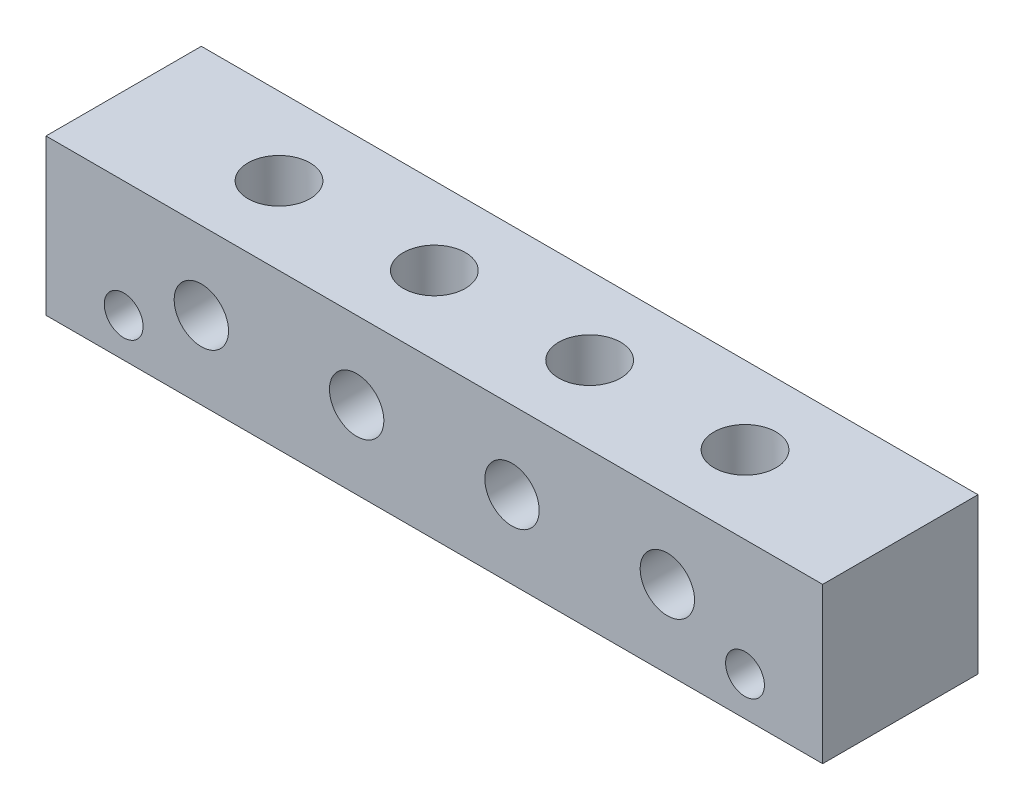
SolidWorks part; units mm, degrees
ref_plane "Plan de face" through (0, 0, 0) normal (0, 0, 1) x (1, 0, 0)
ref_plane "Plan de dessus" through (0, 0, 0) normal (0, 1, 0) x (1, 0, 0)
ref_plane "Plan de droite" through (0, 0, 0) normal (1, 0, 0) x (0, 0, -1)
sketch "Esquisse1" plane through (0, 0, 0) normal (0, 0, 1) x (1, 0, 0)
  line L0 (0, 5) -> (50, 5) construction
  line L1 (0, 0) -> (50, 0)
  line L2 (0, 0) -> (0, 10)
  line L3 (0, 10) -> (50, 10)
  line L4 (50, 0) -> (50, 10)
  line L5 (50, 2.5) -> (0, 2.5) construction
  circle A0 centre (5, 2.5) radius 1.25
  circle A1 centre (45, 2.5) radius 1.25
  circle A2 centre (40, 5) radius 1.75
  circle A3 centre (30, 5) radius 1.75
  circle A4 centre (20, 5) radius 1.75
  circle A5 centre (10, 5) radius 1.75
  point P10 (0, 5)
  point P14 (25, 5)
  dimension "D6" = 2.5
  dimension "D8" = 3.5
  dimension "D1" = 10
  dimension "D2" = 50
  dimension "D3" = 2.5
  dimension "D4" = 40
  dimension "D5" = 5
  dimension "D7" = 15
  dimension "D9" = 4
extrude "Boss.-Extru.1" add sketch "Esquisse1" along normal blind 10
sketch "Esquisse2" plane through (0, 0, 0) normal (0, -1, 0) x (1, 0, 0)
  line L0 (0, 5) -> (50, 5) construction
  line L1 (0, 10) -> (0, 0) construction
  line L2 (50, 10) -> (50, 0) construction
  line L3 (25, 0) -> (25, 10) construction
  line L4 (0, 0) -> (50, 0) construction
  line L5 (0, 10) -> (50, 10) construction
  circle A0 centre (40, 5) radius 2
  circle A1 centre (30, 5) radius 2
  circle A2 centre (20, 5) radius 2
  circle A3 centre (10, 5) radius 2
  dimension "D1" = 25
  dimension "D2" = 15
  dimension "D3" = 4
extrude "Enlèv. mat.-Extru.1" cut sketch "Esquisse2" against normal blind 10
